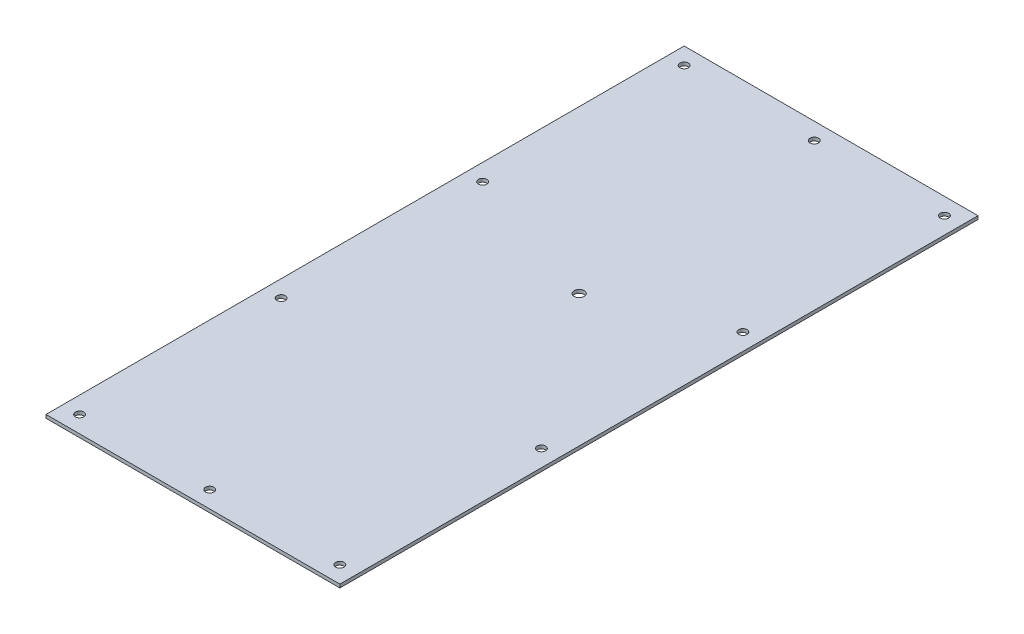
SolidWorks part; units mm, degrees
material "3.1645 (EN-AW 2030)"
ref_plane "Přední rovina" through (0, 0, 0) normal (0, 0, 1) x (1, 0, 0)
ref_plane "Horní rovina" through (0, 0, 0) normal (0, 1, 0) x (1, 0, 0)
ref_plane "Pravá rovina" through (0, 0, 0) normal (1, 0, 0) x (0, 0, -1)
sketch "Skica1" plane through (0, 0, 0) normal (0, 1, 0) x (1, 0, 0)
  line L1 (87.5, -190) -> (-87.5, -190)
  line L2 (87.5, -190) -> (87.5, 190)
  line L3 (87.5, 190) -> (-87.5, 190)
  line L4 (-87.5, -190) -> (-87.5, 190)
  line L5 (87.5, -190) -> (-87.5, 190) construction
  line L6 (87.5, 190) -> (-87.5, -190) construction
  circle A0 centre (-77.5, 180) radius 2.5
  circle A1 centre (0, 180) radius 2.5
  circle A2 centre (77.5, 180) radius 2.5
  circle A4 centre (77.5, 60) radius 2.5
  circle A6 centre (77.5, -60) radius 2.5
  circle A7 centre (0, -180) radius 2.5
  circle A8 centre (77.5, -180) radius 2.5
  circle A9 centre (-77.5, 60) radius 2.5
  circle A10 centre (-77.5, -60) radius 2.5
  circle A11 centre (-77.5, -180) radius 2.5
  circle A12 centre (0, 60) radius 2.5 [skipped]
  circle A13 centre (0, -60) radius 2.5 [skipped]
  point P0 (0, 0)
  dimension "D3" = 5
  dimension "D1" = 175
  dimension "D2" = 380
  dimension "D4" = 10
  dimension "D5" = 10
  dimension "D6" = 3
  dimension "D7" = 4
extrude "Přidat vysunutím1" add sketch "Skica1" along normal blind 2
sketch "Skica2" plane through (0, 2, 0) normal (0, 1, 0) x (1, 0, 0)
  circle A0 centre (8.8969, 31.1064) radius 3
  dimension "D1" = 6
extrude "Odebrat vysunutím1" cut sketch "Skica2" against normal blind 2
